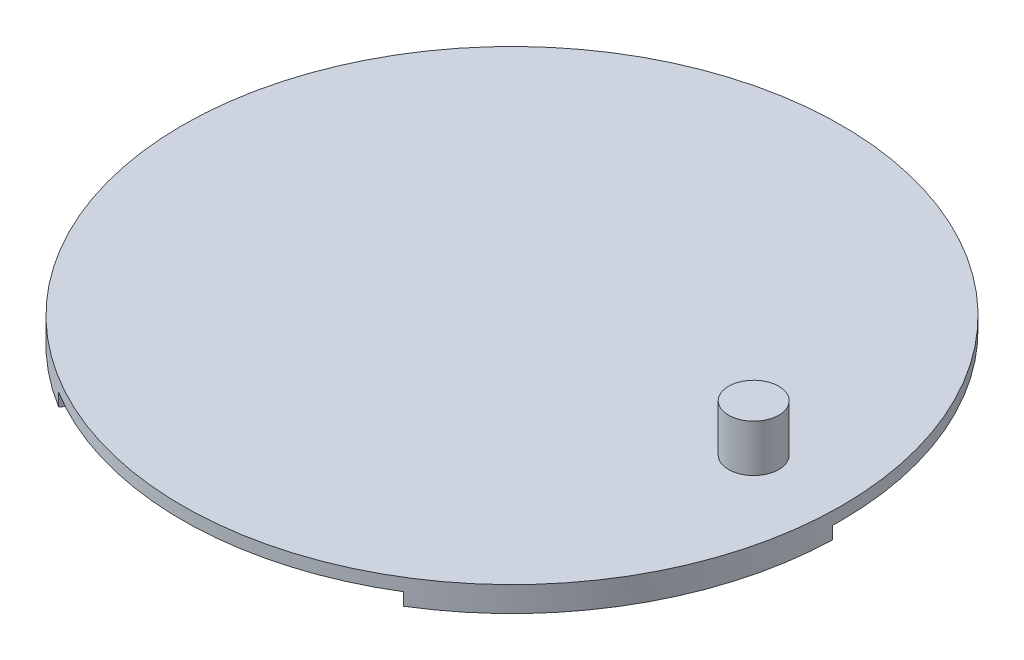
SolidWorks part; units mm, degrees
ref_plane "Front Plane" through (0, 0, 0) normal (0, 0, 1) x (1, 0, 0)
ref_plane "Top Plane" through (0, 0, 0) normal (0, 1, 0) x (1, 0, 0)
ref_plane "Right Plane" through (0, 0, 0) normal (1, 0, 0) x (0, 0, -1)
sketch "Sketch1" plane through (0, 0, 0) normal (0, 0, 1) x (1, 0, 0)
  line L0 (105, 8) -> (0, 8)
  line L1 (0, 8) -> (0, 0)
  line L2 (0, 0) -> (105, 0)
  line L3 (105, 0) -> (105, 8)
  line L4 (0, 8) -> (0, 0) construction
revolve "Revolve1" add sketch "Sketch1" angle 360 about L4
sketch "Sketch2" plane through (0, 0, 0) normal (0, -1, 0) x (1, 0, 0)
  line L0 (47.4888, 79.3792) -> (54.9609, 89.4667)
  line L1 (104.9609, 2.8642) -> (92.4888, 1.4369)
  arc A0 (54.9609, 89.4667) -> (104.9609, 2.8642) centre (0, 0) ccw
  arc A1 (92.4888, 1.4369) -> (47.4888, 79.3792) centre (0, 0) ccw
extrude "Cut-Extrude1" cut sketch "Sketch2" against normal blind 4
sketch "Sketch3" plane through (0, 4, 0) normal (0, -1, 0) x (1, 0, 0)
  line L0 (-92.4888, 1.4369) -> (-104.9609, 2.8642)
  line L1 (-54.9609, 89.4667) -> (-47.4888, 79.3792)
  arc A0 (-104.9609, 2.8642) -> (-54.9609, 89.4667) centre (0, 0) cw
  arc A1 (-47.4888, 79.3792) -> (-92.4888, 1.4369) centre (0, 0) ccw
extrude "Boss-Extrude1" add sketch "Sketch3" along normal blind 4
sketch "Sketch4" plane through (0, 4, 0) normal (0, -1, 0) x (1, 0, 0)
  line L0 (-50, -92.3309) -> (-45, -80.8161)
  line L1 (45, -80.8161) -> (50, -92.3309)
  arc A0 (50, -92.3309) -> (-50, -92.3309) centre (0, 0) cw
  arc A1 (-45, -80.8161) -> (45, -80.8161) centre (0, 0) ccw
extrude "Boss-Extrude2" add sketch "Sketch4" along normal blind 4
sketch "Sketch5" plane through (0, 0, 0) normal (0, 0, 1) x (1, 0, 0)
  line L0 (85, 23) -> (77, 23)
  line L1 (77, 23) -> (77, 8)
  line L2 (77, 8) -> (85, 8)
  line L3 (85, 8) -> (85, 23)
  line L4 (77, 23) -> (77, 8) construction
revolve "Revolve2" add sketch "Sketch5" angle 360 about L4
